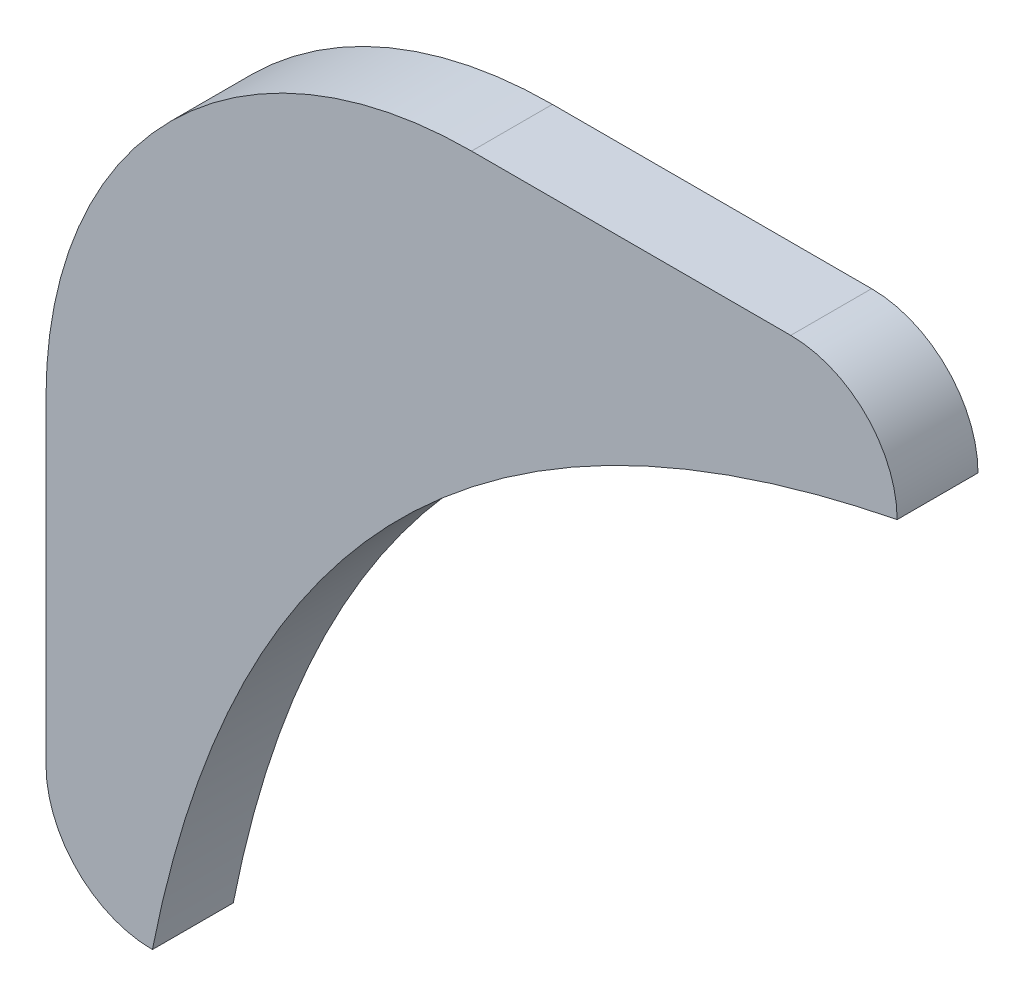
SolidWorks part; units mm, degrees
ref_plane "Front Plane" through (0, 0, 0) normal (0, 0, 1) x (1, 0, 0)
ref_plane "Top Plane" through (0, 0, 0) normal (0, 1, 0) x (1, 0, 0)
ref_plane "Right Plane" through (0, 0, 0) normal (1, 0, 0) x (0, 0, -1)
sketch "Sketch1" plane through (0, 0, 0) normal (0, 0, 1) x (1, 0, 0)
  line L2 (0, 6.35) -> (0, 25.4)
  line L3 (25.4, 50.8) -> (44.45, 50.8)
  arc A0 (44.45, 50.8) -> (50.8, 44.45) centre (44.45, 44.45) cw
  arc A1 (0, 6.35) -> (6.35, 0) centre (6.35, 6.35) ccw
  arc A2 (0, 25.4) -> (25.4, 50.8) centre (25.4, 25.4) cw
  spline S0 degree 2 poles (6.35, 0) (13.6869, 37.0822) (50.8, 44.45) knots 0 0 0 1 1 1
  point P7 (50.8, 50.8)
  point P10 (0, 0)
  point P13 (0, 50.8)
  dimension "D3" = 6.35
  dimension "D4" = 25.4
  dimension "D2" = 50.8
extrude "Boss-Extrude1" add sketch "Sketch1" along normal blind 4.826
equation "\"MDF\"= 0.19in"
equation "\"PVCID\" = 2.067in"
equation "\"PVCOD\" = 2.375in"
equation "\"GenDiameter\"= 60mm"
equation "\"GenCutDiameter\" = 1.8in"
equation "\"GenCutDistance\" = 1"
equation "\"TowerHeight\" = 6in"
equation "\"TowerFrontBase\" = 3in"
equation "\"FunnelHeight\" = 1in"
equation "\"FunnelAngle\" = 20"
equation "\"TowerSideBase\" = 3in"
equation "\"TowerPanelLength\" = 2in"
equation "\"TowerPanelLeeway\" = 0.5in"
equation "\"BaseLength\" = 9in"
equation "\"BaseWidth\" = 10in"
equation "\"WheelHoleLength\" = 3.25in"
equation "\"WheelHoleWidth\" = 26mm"
equation "\"WheelHoleFromBack\" = 1in"
equation "\"DropLength\" = 1in"
equation "\"DropWidth\" = 8.5in"
equation "\"BumperWidth\" = 1in"
equation "\"SmallHexDiameter\" = 0.185in"
equation "\"SmallHexHeight\" = 0.701in"
equation "\"ScrewSize\" = 0.106in"
equation "\"BigHexDiameter\" = 0.251in"
equation "\"BigHexHeight\" = 0.374in"
equation "\"PCBThickness\" = 0.066in"
equation "\"ConnectorHeight\" = 0.517in"
equation "\"BoardHeight\" = 0.583in"
equation "\"UnoStackHeight\" = 1.351in"
equation "\"UnoStackWidth\" = 3.053in"
equation "\"UnoStackLength\" = 3.152in"
equation "\"HBridgeWidth\" = 1.797in"
equation "\"HBridgeLength\" = 2.236in"
equation "\"DSWidth\" = 1.820in"
equation "\"DSLength\" = 1.833in"
equation "\"StepperWidth\" = 1.799in"
equation "\"StepperLength\" = 2.248in"
equation "\"ULNWidth\" = 1.304in"
equation "\"ULNLength\" = 1.545in"
equation "\"VSwitchHeight\" = 0.392in"
equation "\"VSwitchWidth\" = 0.637in"
equation "\"VSwitchLength\" = 1.097in"
equation "\"SkateWheelDiameter\" = 80mm"
equation "\"SkateWheelThickness\" = 24mm"
equation "\"BaseDistance\" = 3in"
equation "\"DummyVar\" = 2in"
equation "\"D1@Boss-Extrude1\"=\"MDF\""
